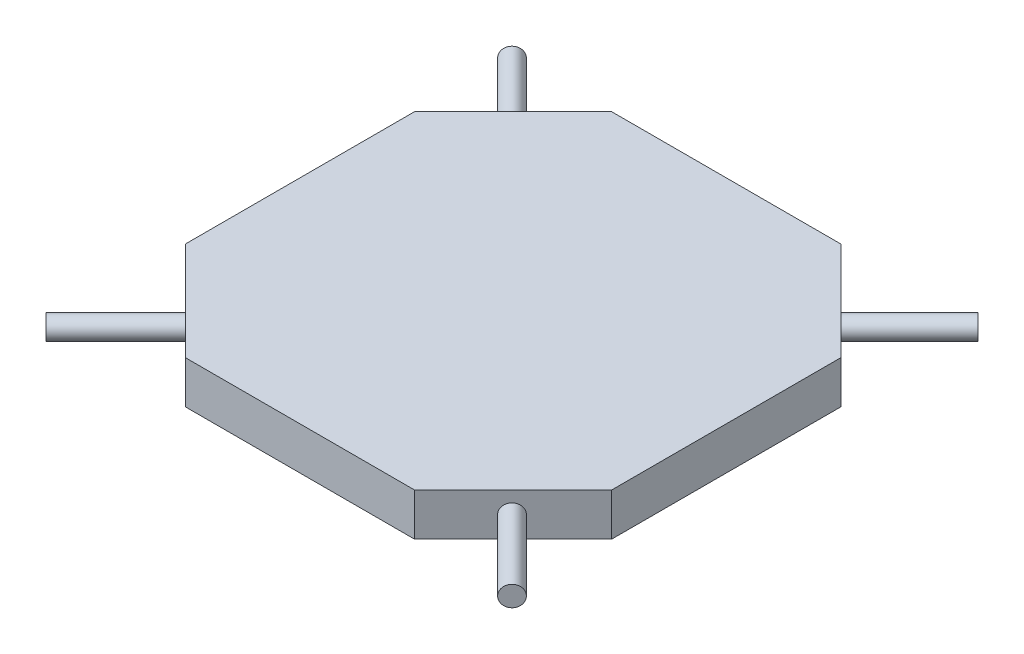
SolidWorks part; units mm, degrees
ref_plane "Front Plane" through (0, 0, 0) normal (0, 0, 1) x (1, 0, 0)
ref_plane "Top Plane" through (0, 0, 0) normal (0, 1, 0) x (1, 0, 0)
ref_plane "Right Plane" through (0, 0, 0) normal (1, 0, 0) x (0, 0, -1)
sketch "Sketch2" plane through (0, 0, 0) normal (0, 1, 0) x (1, 0, 0)
  line L0 (-50.189, 27.3408) -> (-50.189, -26.4427)
  line L1 (-27.0808, -49.551) -> (26.7027, -49.551)
  line L2 (49.811, -26.4427) -> (49.811, 27.3408)
  line L3 (26.7027, 50.449) -> (-27.0808, 50.449)
  line L4 (-0.189, 50.449) -> (-0.189, -49.551) construction
  line L5 (49.811, 0.449) -> (-50.189, 0.449) construction
  line L6 (-50.189, 27.3408) -> (-27.0808, 50.449)
  line L7 (-0.189, 0.449) -> (-38.6349, 38.8949) construction
  line L8 (49.811, 27.3408) -> (26.7027, 50.449)
  line L9 (49.811, -26.4427) -> (26.7027, -49.551)
  line L10 (-50.189, -26.4427) -> (-27.0808, -49.551)
  dimension "D1" = 32.68
extrude "Boss-Extrude1" add sketch "Sketch2" along normal mid plane 10
ref_plane "Plane1" through (38.1269, 0, 38.1269) normal (0.7071, 0, 0.7071) x (0.7071, 0, -0.7071)
sketch "Sketch3" plane through (38.1269, 0, 38.1269) normal (0.7071, 0, 0.7071) x (0.7071, 0, -0.7071)
  line L0 (0, 0) -> (2.098, 1.1447) construction
  circle A0 centre (0, 0) radius 2.39
  dimension "D1" = 2.39
extrude "Boss-Extrude2" add sketch "Sketch3" along normal blind 23.4
mirror "Mirror2" about plane through (0, 0, 0) normal (1, 0, 0) of "Boss-Extrude2"
mirror "Mirror3" about plane through (0, 0, 0) normal (0, 0, 1) of "Mirror2", "Boss-Extrude2"
